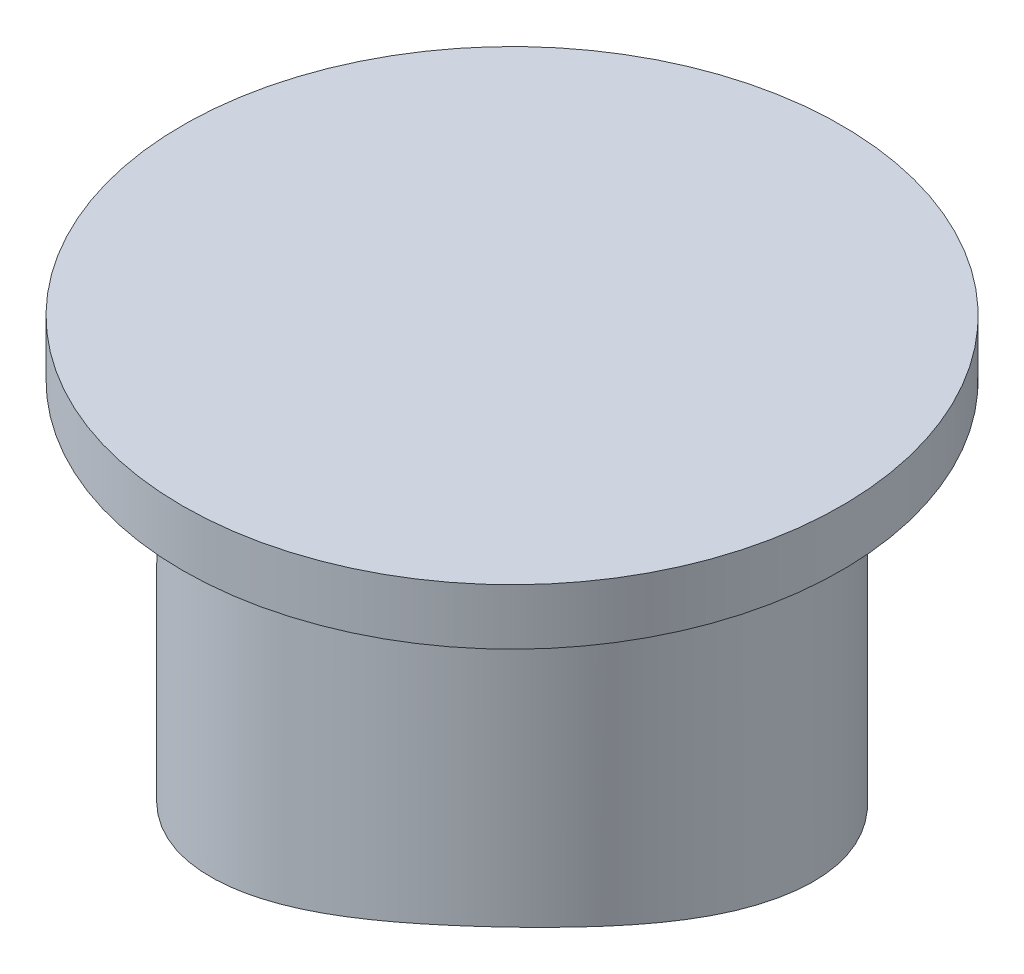
SolidWorks part; units mm, degrees
ref_plane "Ön Düzlem" through (0, 0, 0) normal (0, 0, 1) x (1, 0, 0)
ref_plane "Üst Düzlem" through (0, 0, 0) normal (0, 1, 0) x (1, 0, 0)
ref_plane "Sağ Düzlem" through (0, 0, 0) normal (1, 0, 0) x (0, 0, -1)
sketch "Sketch2" plane through (0, 0, 0) normal (0, 1, 0) x (1, 0, 0)
  circle A0 centre (0, 0) radius 29.5
  dimension "D1" = 59
extrude "Boss-Extrude1" add sketch "Sketch2" along normal blind 5
sketch "Sketch3" plane through (0, 0, 0) normal (0, -1, 0) x (1, 0, 0)
  circle A0 centre (0, 0) radius 22.5
  dimension "D1" = 45
extrude "Boss-Extrude2" add sketch "Sketch3" along normal blind 100
sketch "Sketch4" plane through (-63.9962, 0, 59.6719) normal (-0.7314, 0, 0.682) x (0.682, 0, 0.7314)
  line L3 (-29.1254, -34.1695) -> (-29.1254, -106.9933)
  line L4 (-29.1254, -106.9933) -> (28.3337, -106.9933)
  line L5 (28.3337, -106.9933) -> (28.3337, -22.4964)
  spline S0 degree 3 poles (-29.1254, -34.1695) (-19.0275, -34.2272) (-4.4808, -34.0282) (14.9267, -29.7721) (24.2569, -26.2835) (28.3337, -22.4964) knots 0 0 0 0 0.508724 0.724603 1 1 1 1
  point P2 (0, 0)
  point P8 (0, 0)
  point P10 (0, 0)
  point P11 (0, 0)
  point P14 (0, 0)
  point P15 (0, 0)
  point P16 (0, 0)
  point P17 (0, 0)
extrude "Cut-Extrude1" cut sketch "Sketch4" against normal blind 181
